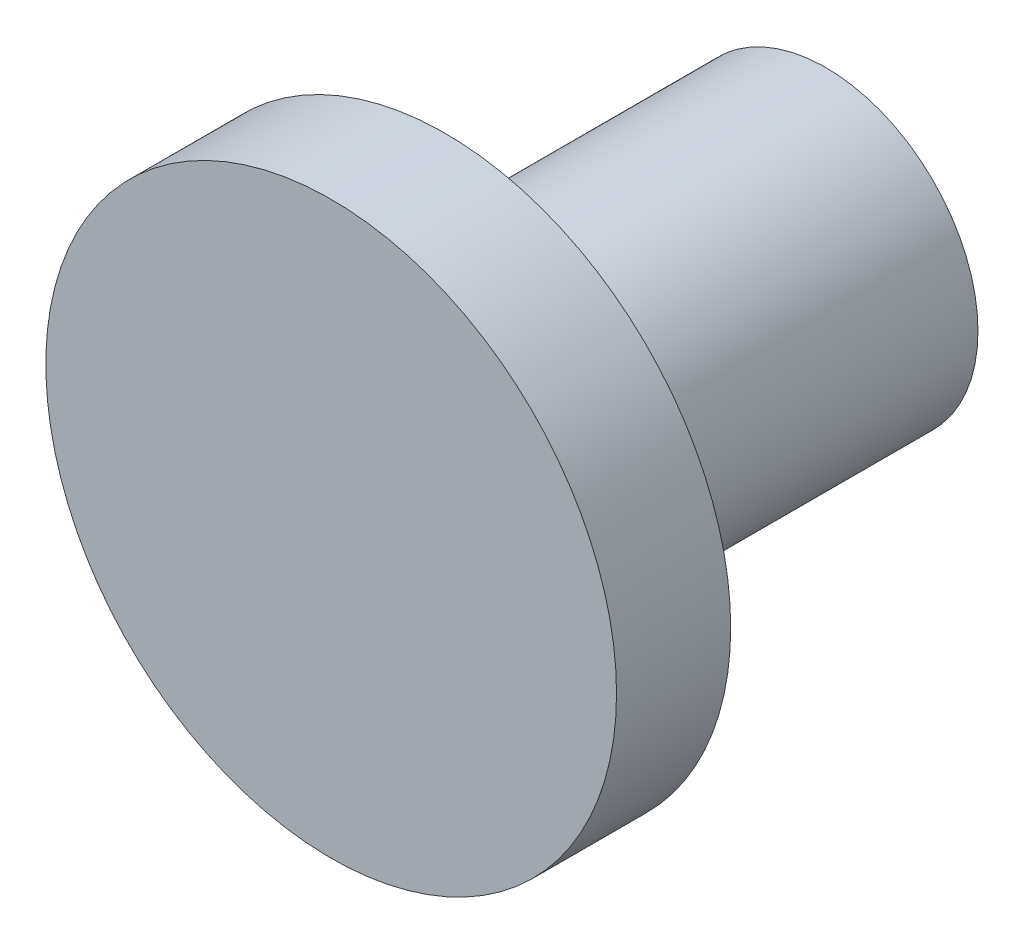
SolidWorks part; units mm, degrees
material "Brass"
ref_plane "Front Plane" through (0, 0, 0) normal (0, 0, 1) x (1, 0, 0)
ref_plane "Top Plane" through (0, 0, 0) normal (0, 1, 0) x (1, 0, 0)
ref_plane "Right Plane" through (0, 0, 0) normal (1, 0, 0) x (0, 0, -1)
sketch "Sketch1" plane through (0, 0, 0) normal (0, 0, 1) x (1, 0, 0)
  circle A0 centre (0, 0) radius 4
  dimension "D1" = 8
extrude "Boss-Extrude1" add sketch "Sketch1" along normal blind 10
sketch "Sketch2" plane through (0, 0, 10) normal (0, 0, 1) x (1, 0, 0)
  circle A0 centre (0, 0) radius 7.5
  dimension "D1" = 15
extrude "Boss-Extrude2" add sketch "Sketch2" along normal blind 3
sketch "Sketch3" plane through (0, 0, 0) normal (0, 0, -1) x (-1, 0, 0)
  circle A0 centre (0, 0) radius 1.25
  dimension "D1" = 2.5
extrude "Cut-Extrude1" cut sketch "Sketch3" against normal blind 10
cosmetic thread "Cosmetic Thread1" parameters "D1"=5, "D2"=3
